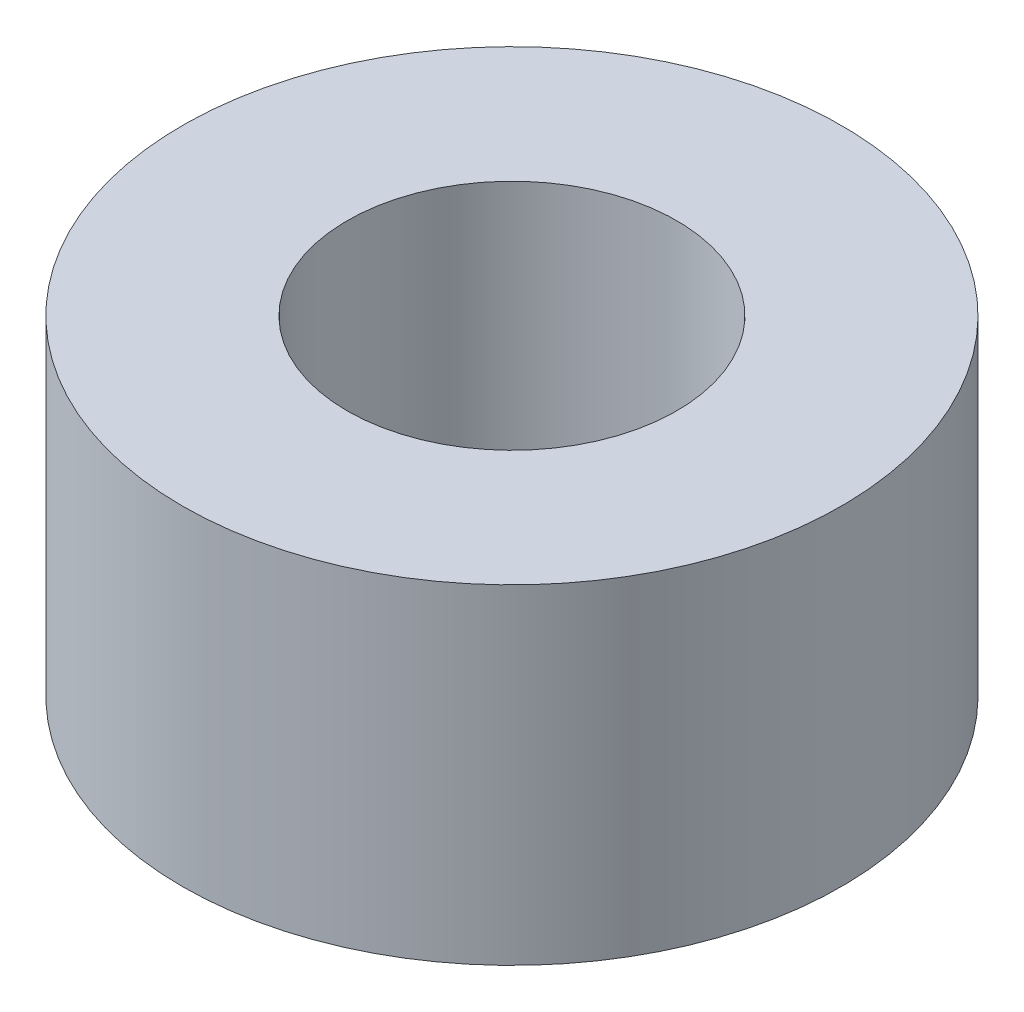
SolidWorks part; units mm, degrees
material "Malleable Cast Iron"
ref_plane "Front Plane" through (0, 0, 0) normal (0, 0, 1) x (1, 0, 0)
ref_plane "Top Plane" through (0, 0, 0) normal (0, 1, 0) x (1, 0, 0)
ref_plane "Right Plane" through (0, 0, 0) normal (1, 0, 0) x (0, 0, -1)
sketch "Sketch1" plane through (0, 0, 0) normal (0, 1, 0) x (1, 0, 0)
  circle A0 centre (0, 0) radius 20
  circle A1 centre (0, 0) radius 40
  dimension "D1" = 80
  dimension "D2" = 40
extrude "Boss-Extrude1" add sketch "Sketch1" along normal blind 40
